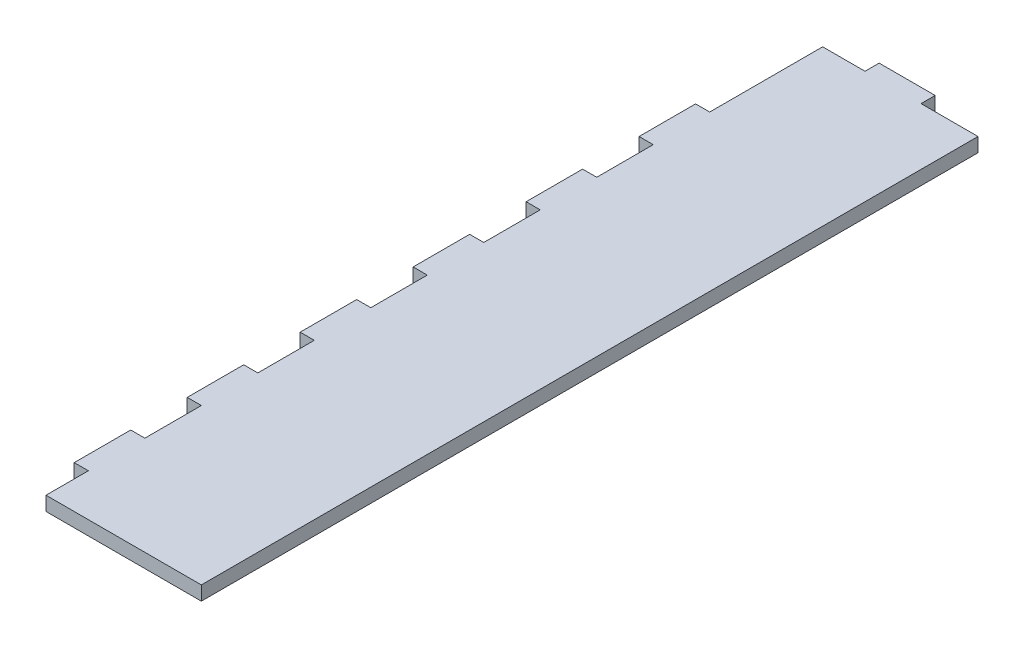
SolidWorks part; units mm, degrees
ref_plane "Front Plane" through (0, 0, 0) normal (0, 0, 1) x (1, 0, 0)
ref_plane "Top Plane" through (0, 0, 0) normal (0, 1, 0) x (1, 0, 0)
ref_plane "Right Plane" through (0, 0, 0) normal (1, 0, 0) x (0, 0, -1)
sketch "Sketch1" plane through (0, 0, 0) normal (0, 1, 0) x (1, 0, 0)
  line L1 (19.05, -88.9) -> (-19.05, -88.9)
  line L2 (19.05, -88.9) -> (19.05, 88.9)
  line L3 (19.05, 88.9) -> (-19.05, 88.9)
  line L4 (-19.05, -88.9) -> (-19.05, 88.9)
  line L5 (19.05, -88.9) -> (-19.05, 88.9) construction
  line L6 (19.05, 88.9) -> (-19.05, -88.9) construction
  point P0 (0, 0)
  dimension "D1" = 177.8
  dimension "D2" = 38.1
extrude "Boss-Extrude1" add sketch "Sketch1" along normal blind 3.175
sketch "Sketch2" plane through (0, 3.175, 0) normal (0, 1, 0) x (1, 0, 0)
  line L0 (19.05, 88.9) -> (-19.05, 88.9) construction
  line L2 (-6.35, 88.9) -> (-6.35, 85.725)
  line L6 (-19.05, 88.9) -> (-19.05, -88.9) construction
  line L7 (-19.05, 60.325) -> (-15.875, 60.325)
  line L8 (-19.05, 60.325) -> (-19.05, 88.9)
  line L9 (-19.05, 88.9) -> (-15.875, 88.9)
  line L11 (-19.05, 22.225) -> (-19.05, 9.525)
  line L12 (-19.05, 47.625) -> (-15.875, 47.625)
  line L13 (-19.05, 47.625) -> (-19.05, 34.925)
  line L14 (-19.05, 34.925) -> (-15.875, 34.925)
  line L15 (-15.875, 47.625) -> (-15.875, 34.925)
  line L16 (-19.05, 22.225) -> (-15.875, 22.225)
  line L17 (-15.875, 22.225) -> (-15.875, 9.525)
  line L18 (-19.05, 9.525) -> (-15.875, 9.525)
  line L19 (-19.05, -3.175) -> (-19.05, -15.875)
  line L20 (-19.05, -3.175) -> (-15.875, -3.175)
  line L21 (-15.875, -3.175) -> (-15.875, -15.875)
  line L22 (-19.05, -15.875) -> (-15.875, -15.875)
  line L23 (-19.05, -28.575) -> (-19.05, -41.275)
  line L24 (-19.05, -28.575) -> (-15.875, -28.575)
  line L25 (-15.875, -28.575) -> (-15.875, -41.275)
  line L26 (-19.05, -41.275) -> (-15.875, -41.275)
  line L27 (-19.05, -53.975) -> (-19.05, -66.675)
  line L28 (-19.05, -53.975) -> (-15.875, -53.975)
  line L29 (-15.875, -53.975) -> (-15.875, -66.675)
  line L30 (-19.05, -66.675) -> (-15.875, -66.675)
  line L32 (-19.05, -79.375) -> (-15.875, -79.375)
  line L35 (-19.05, -92.075) -> (-15.875, -92.075) [skipped]
  line L36 (-15.875, -79.375) -> (-15.875, -92.075) [skipped]
  line L37 (-19.05, -79.375) -> (-19.05, -92.075) [skipped]
  line L38 (-15.875, -79.375) -> (-15.875, -88.9)
  line L39 (-19.05, -88.9) -> (19.05, -88.9) construction
  line L40 (-15.875, -88.9) -> (-19.05, -88.9)
  line L41 (-19.05, -88.9) -> (-19.05, -79.375)
  line L42 (-6.35, 85.725) -> (-15.875, 85.725)
  line L43 (-15.875, 88.9) -> (-6.35, 88.9)
  line L44 (19.05, 88.9) -> (6.2407, 88.9)
  line L45 (6.2407, 88.9) -> (6.2407, 85.725)
  line L46 (-15.875, 85.725) -> (-15.875, 60.325)
  line L47 (6.2407, 85.725) -> (19.05, 85.725)
  line L48 (19.05, -88.9) -> (19.05, 88.9) construction
  line L49 (19.05, 85.725) -> (19.05, 88.9)
  dimension "D4" = 28.575
  dimension "D5" = 12.7
  dimension "D6" = 12.7
  dimension "D7" = 3.175
  dimension "D8" = 3.175
  dimension "D9" = 6
extrude "Cut-Extrude1" cut sketch "Sketch2" against normal blind 3.175
